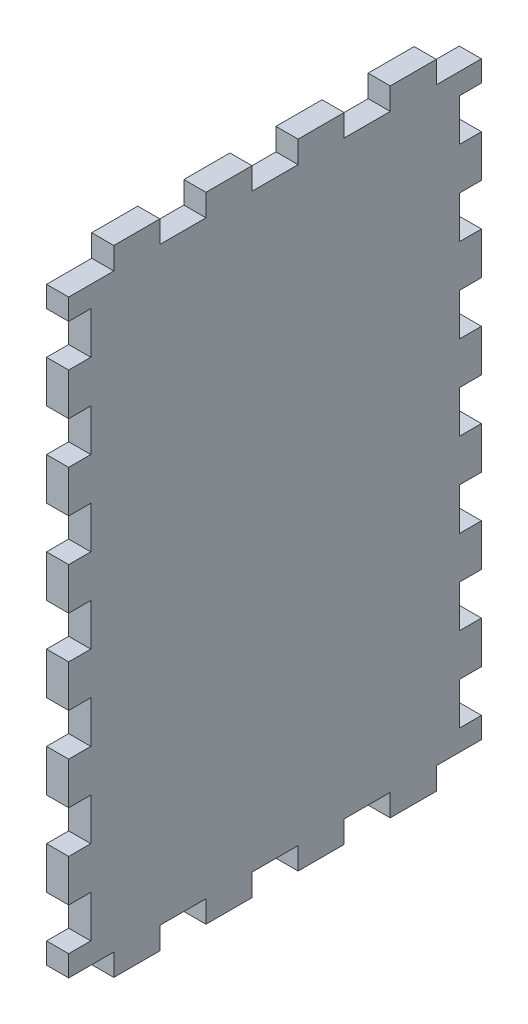
SolidWorks part; units mm, degrees
ref_plane "Piano frontale" through (0, 0, 0) normal (0, 0, 1) x (1, 0, 0)
ref_plane "Piano superiore" through (0, 0, 0) normal (0, 1, 0) x (1, 0, 0)
ref_plane "Piano destro" through (0, 0, 0) normal (1, 0, 0) x (0, 0, -1)
sketch "Schizzo1" plane through (0, 0, 0) normal (1, 0, 0) x (0, 0, -1)
  line L1 (0, 0) -> (50, 0)
  line L2 (0, 0) -> (0, 80)
  line L3 (0, 80) -> (50, 80)
  line L4 (50, 0) -> (50, 80)
  dimension "D1" = 80
  dimension "D2" = 50
extrude "Estrusione-Estrusione1" add sketch "Schizzo1" along normal blind 3
sketch "Schizzo2" plane through (3, 0, 0) normal (1, 0, 0) x (0, 0, -1)
  line L0 (0, 80) -> (0, 0) construction
  line L1 (0, 77.1429) -> (-3, 77.1429)
  line L2 (0, 77.1429) -> (0, 80)
  line L3 (0, 80) -> (-3, 80)
  line L4 (-3, 77.1429) -> (-3, 80)
  line L6 (50, 80) -> (53, 80)
  line L7 (50, 80) -> (50, 77.1429)
  line L8 (50, 77.1429) -> (53, 77.1429)
  line L9 (53, 80) -> (53, 77.1429)
  line L10 (50, 0) -> (53, 0)
  line L11 (50, 0) -> (50, 2.8571)
  line L12 (50, 2.8571) -> (53, 2.8571)
  line L13 (53, 0) -> (53, 2.8571)
  line L14 (0, 0) -> (-3, 0)
  line L15 (0, 0) -> (0, 2.8571)
  line L16 (0, 2.8571) -> (-3, 2.8571)
  line L17 (-3, 0) -> (-3, 2.8571)
  point P21 (0, 0)
  dimension "D1" = 3
  dimension "D2" = 3
  dimension "D3" = 2.8571
  dimension "D4" = 2.8571
extrude "Estrusione-Estrusione2" add sketch "Schizzo2" against normal blind 3
sketch "Schizzo3" plane through (3, 0, 0) normal (1, 0, 0) x (0, 0, -1)
  line L0 (0, 77.1429) -> (0, 2.8571) construction
  line L1 (0, 71.4286) -> (-3, 71.4286)
  line L2 (0, 71.4286) -> (0, 65.7143)
  line L3 (0, 65.7143) -> (-3, 65.7143)
  line L4 (-3, 71.4286) -> (-3, 65.7143)
  line L5 (50, 2.8571) -> (50, 77.1429) construction
  line L6 (50, 71.4286) -> (53, 71.4286)
  line L7 (50, 71.4286) -> (50, 65.7143)
  line L8 (50, 65.7143) -> (53, 65.7143)
  line L9 (53, 71.4286) -> (53, 65.7143)
  line L10 (-3, 77.1429) -> (0, 77.1429) construction
  line L11 (-3, 80) -> (-3, 77.1429) construction
  line L12 (53, 77.1429) -> (53, 80) construction
  dimension "D1" = 5.7143
  dimension "D2" = 5.7143
extrude "Estrusione-Estrusione3" add sketch "Schizzo3" against normal blind 3
pattern_linear "Ripetizione a L1" count 6 spacing 11.4286 along (0, -1, 0) of "Estrusione-Estrusione3"
sketch "Schizzo4" plane through (3, 0, 0) normal (1, 0, 0) x (0, 0, -1)
  line L0 (53, 80) -> (-3, 80) construction
  line L1 (3.125, 80) -> (9.375, 80)
  line L2 (3.125, 80) -> (3.125, 83)
  line L3 (3.125, 83) -> (9.375, 83)
  line L4 (9.375, 80) -> (9.375, 83)
  line L5 (-3, 0) -> (53, 0) construction
  line L6 (3.125, 0) -> (9.375, 0)
  line L7 (3.125, 0) -> (3.125, -3)
  line L8 (3.125, -3) -> (9.375, -3)
  line L9 (9.375, 0) -> (9.375, -3)
  line L10 (0, 77.1429) -> (0, 71.4286) construction
  point P14 (6.25, 0)
  dimension "D1" = 3.125
  dimension "D2" = 6.25
  dimension "D3" = 3
  dimension "D4" = 3
extrude "Estrusione-Estrusione4" add sketch "Schizzo4" against normal blind 3
pattern_linear "Ripetizione a L2" count 4 spacing 12.5 along (0, 0, -1) of "Estrusione-Estrusione4"
equation "\"WFront\"= 140mm"
equation "\"HFront\"= 80mm"
equation "\"DFront\"= 3mm"
equation "\"WLeft\"= 50mm"
equation "\"HLeft\"= 80mm"
equation "\"DLeft\"= 3mm"
equation "\"WTop\"= 140mm"
equation "\"HTop\"= 50mm"
equation "\"DTop\"= 3mm"
equation "\"N_Denti_W\"= 10"
equation "\"N_Denti_H\"= 7"
equation "\"N_Denti_D\"= 4"
equation "\"HDistDenti\"= \"HFront\" / \"N_Denti_H\""
equation "\"WDistDenti\"= \"WFront\" / \"N_Denti_W\""
equation "\"DDistDenti\"= \"WLeft\" / \"N_Denti_D\""
equation "\"HDenti\"= \"HDistDenti\" / 2"
equation "\"WDenti\"= \"WDistDenti\" / 2"
equation "\"DDenti\"= \"DDistDenti\" / 2"
equation "\"WDisplay\"= 95mm"
equation "\"HDisplay\"= 61mm"
equation "\"CEnc\"= 7mm"
equation "\"Display_to_Enc_W\"= 11.5 + \"CEnc\" / 2"
equation "\"Display_to_Dx\"= 32mm"
equation "\"Display_to_Top\"= 10mm"
equation "\"Display_to_Enc_H\"= 24 + \"CEnc\" / 2"
equation "\"D1@Schizzo1\"=\"HLeft\""
equation "\"D2@Schizzo1\"=\"WLeft\""
equation "\"D1@Estrusione-Estrusione1\"=\"DLeft\""
equation "\"D1@Schizzo2\"=\"DFront\""
equation "\"D2@Schizzo2\"=\"DFront\""
equation "\"D3@Schizzo2\"=\"HDenti\"/2"
equation "\"D4@Schizzo2\"=\"HDenti\"/2 "
equation "\"D1@Estrusione-Estrusione2\"=\"DLeft\""
equation "\"D1@Schizzo3\"=\"HDenti\""
equation "\"D2@Schizzo3\"=\"HDenti\""
equation "\"D1@Estrusione-Estrusione3\"=\"DLeft\""
equation "\"D1@Ripetizione a L1\"=\"N_Denti_H\"-1"
equation "\"D1@Schizzo4\"=\"DDenti\"/2"
equation "\"D2@Schizzo4\"=\"DDenti\""
equation "\"D3@Schizzo4\"=\"DTop\""
equation "\"D4@Schizzo4\"=\"DTop\""
equation "\"D1@Estrusione-Estrusione4\"=\"DLeft\""
equation "\"D3@Ripetizione a L2\"=\"DDistDenti\""
equation "\"D1@Ripetizione a L2\"=\"N_Denti_D\""
